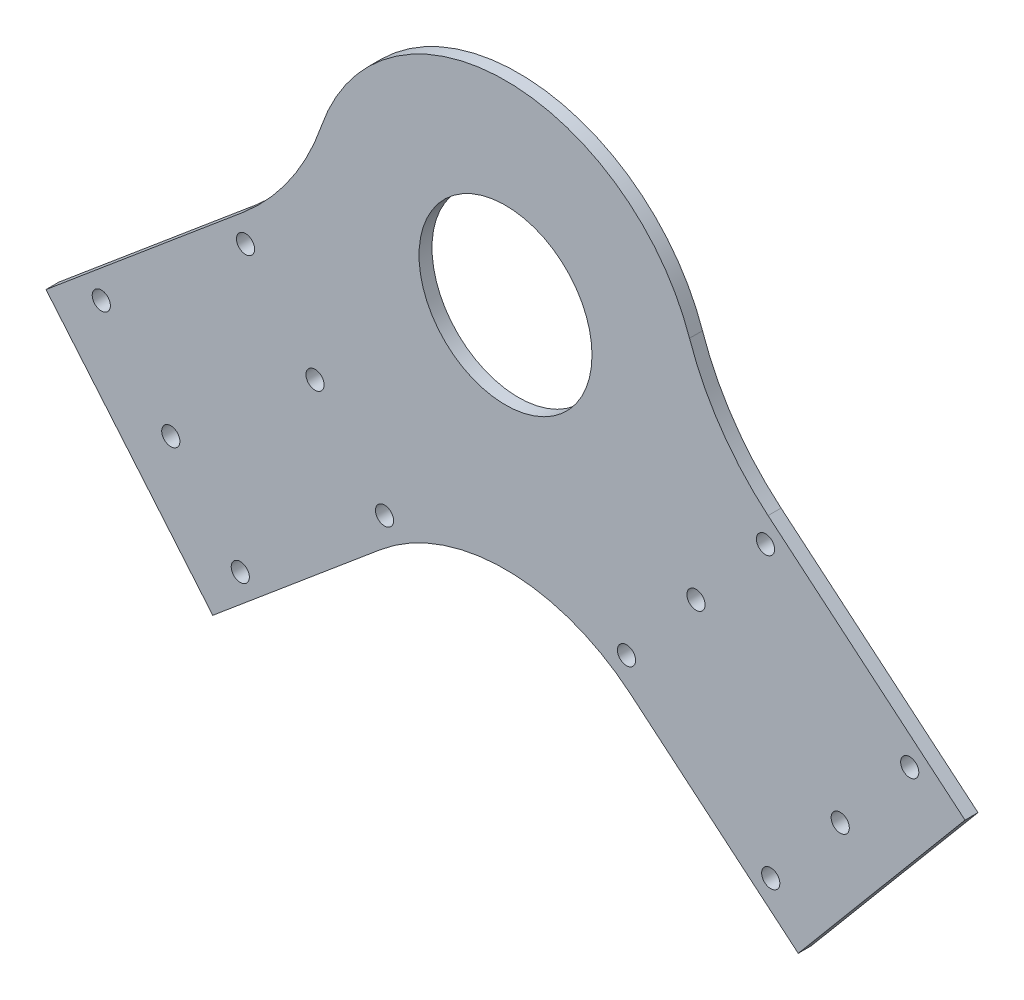
SolidWorks part; units mm, degrees
ref_plane "Front Plane" through (0, 0, 0) normal (0, 0, 1) x (1, 0, 0)
ref_plane "Top Plane" through (0, 0, 0) normal (0, 1, 0) x (1, 0, 0)
ref_plane "Right Plane" through (0, 0, 0) normal (1, 0, 0) x (0, 0, -1)
sketch "Sketch1" plane through (0, 0, 0) normal (0, 0, 1) x (1, 0, 0)
  line L0 (0, 0) -> (0, 50000) construction
  line L1 (0, 0) -> (50000, 0) construction
  line L2 (0, 0) -> (-1203.5328, -1009.8839) construction
  line L3 (-67.6938, -95.9641) -> (-6.4103, -44.5411)
  line L4 (-67.6938, -95.9641) -> (-106.2611, -50.0014)
  line L6 (-106.2611, -50.0014) -> (-44.9775, 1.4216)
  line L7 (67.6938, -95.9641) -> (106.2611, -50.0014)
  line L8 (106.2611, -50.0014) -> (44.9775, 1.4216)
  line L9 (67.6938, -95.9641) -> (6.4103, -44.5411)
  line L10 (-6.4103, -44.5411) -> (0, -39.1622)
  line L11 (6.4103, -44.5411) -> (0, -39.1622)
  line L12 (96.6855, -41.9666) -> (58.1183, -87.9292) construction
  line L13 (63.332, -13.9796) -> (24.7647, -59.9423) construction
  arc A0 (6.4103, -44.5411) -> (-6.4103, -44.5411) centre (0, 0) ccw
  circle A1 centre (0, 0) radius 20
  circle A2 centre (93.4716, -45.7968) radius 2.1
  circle A3 centre (77.4019, -64.9479) radius 2.1
  circle A4 centre (61.3322, -84.099) radius 2.1
  circle A5 centre (-61.3322, -84.099) radius 2.1
  circle A6 centre (-77.4019, -64.9479) radius 2.1
  circle A7 centre (-93.4716, -45.7968) radius 2.1
  circle A8 centre (60.118, -17.8098) radius 2.1
  circle A9 centre (44.0483, -36.9609) radius 2.1
  circle A10 centre (27.9786, -56.1121) radius 2.1
  circle A11 centre (-27.9786, -56.1121) radius 2.1
  circle A12 centre (-44.0483, -36.9609) radius 2.1
  circle A13 centre (-60.118, -17.8098) radius 2.1
  dimension "D1" = 90
  dimension "D2" = 50
  dimension "D6" = 40
  dimension "D8" = 4.2
  dimension "D3" = 30
  dimension "D4" = 30
  dimension "D5" = 80
  dimension "D7" = 12.5
  dimension "D9" = 5
  dimension "D10" = 5
  dimension "D11" = 43.54
  dimension "D12" = 5
  dimension "D13" = 5
extrude "Boss-Extrude1" add sketch "Sketch1" along normal blind 3 contours A0 | A0 L6 L4 L3 L9 | A0 L3 L9 L7 L8 | A0 L9 L3
fillet "Fillet1" radius 60 2 edges at (44.9775, 1.4216, 1.5) (-44.9775, 1.4216, 1.5)
fillet "Fillet3" radius 45 1 edges at (0, -39.1622, 1.5)
